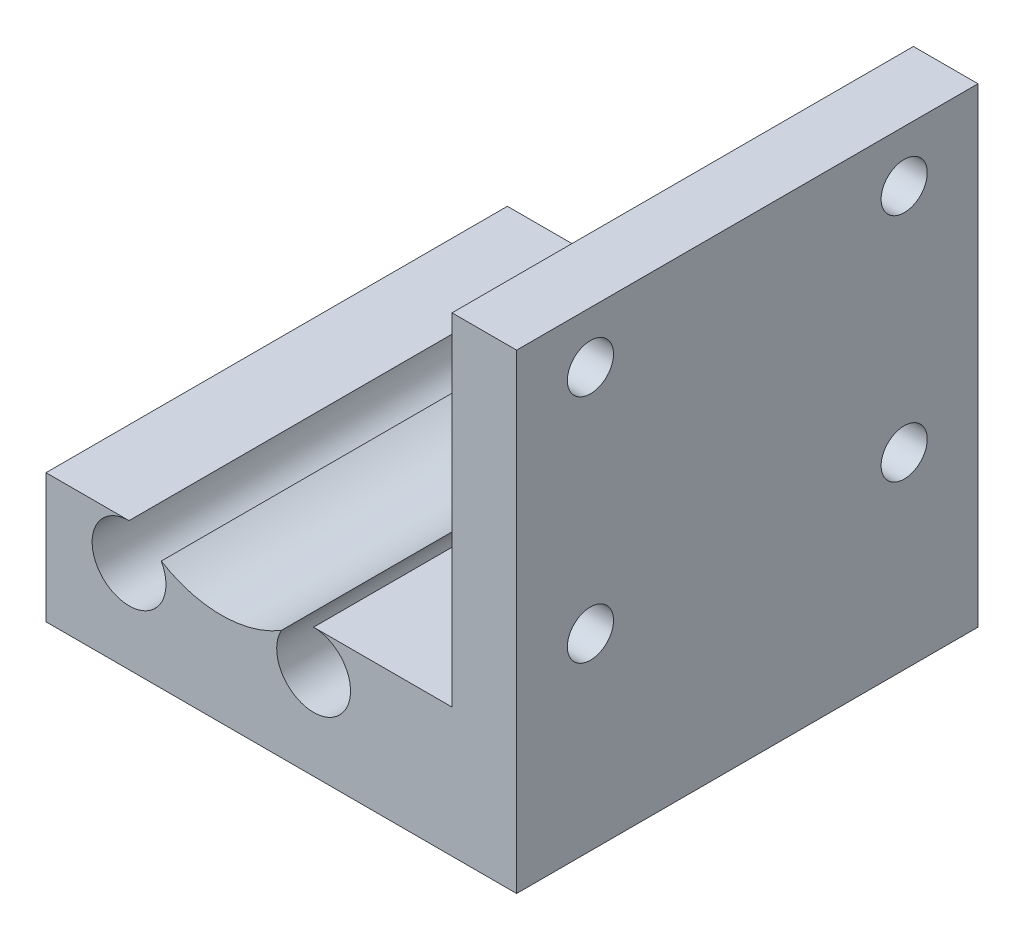
SolidWorks part; units mm, degrees
material "3.0517 (EN-AW 3003)"
ref_plane "Front Plane" through (0, 0, 0) normal (0, 0, 1) x (1, 0, 0)
ref_plane "Top Plane" through (0, 0, 0) normal (0, 1, 0) x (1, 0, 0)
ref_plane "Right Plane" through (0, 0, 0) normal (1, 0, 0) x (0, 0, -1)
sketch "Sketch1" plane through (0, 0, 0) normal (0, 0, 1) x (1, 0, 0)
  line L0 (0, 18.7548) -> (0, -19.4032) construction
  line L1 (-10, -9.1244) -> (-19, -9.1244)
  line L2 (-19, -9.1244) -> (-19, -23.1244)
  line L3 (-19, -23.1244) -> (32, -23.1244)
  line L5 (32, 27.8756) -> (25, 27.8756)
  line L6 (25, 27.8756) -> (25, -9.1244)
  line L7 (25, -9.1244) -> (10, -9.1244)
  line L11 (-23.1238, -13.7244) -> (85.8792, -13.7244) construction
  line L15 (32, 27.8756) -> (32, -23.1244)
  circle A1 centre (0, 0) radius 12.5 construction
  arc A2 (6.5091, -11.1715) -> (10, -9.1244) centre (10, -13.1244) ccw
  arc A4 (-6.5091, -11.1715) -> (-10, -9.1244) centre (-10, -13.1244) cw
  circle A5 centre (0, 11.4164) radius 22.5 construction
  arc A6 (-6.5091, -11.1715) -> (6.5091, -11.1715) centre (0, -0.5) ccw
  circle A8 centre (-10, -13.1244) radius 4 construction
  circle A9 centre (10, -13.1244) radius 4 construction
  dimension "D1" = 25
  dimension "D2" = 8
  dimension "D3" = 10
  dimension "D4" = 45
  dimension "D5" = 12.5
  dimension "D6" = 0.5
  dimension "D7" = 9
  dimension "D8" = 14
  dimension "D9" = 51
  dimension "D10" = 15
  dimension "D12" = 7
  dimension "D14" = 9.4
extrude "Boss-Extrude1" add sketch "Sketch1" along normal mid plane 50
sketch "Sketch5" plane through (32, 0, 0) normal (1, 0, 0) x (0, 0, -1)
  line L0 (0, 45.8756) -> (0, -19.1244) construction
  line L1 (0, 27.8756) -> (0, -23.1244) construction
  line L2 (-25, 2.3756) -> (25, 2.3756) construction
  line L3 (-25, -23.1244) -> (-25, 27.8756) construction
  line L4 (25, -23.1244) -> (25, 27.8756) construction
  line L5 (17, 2.3756) -> (17, -23.1244) construction
  line L6 (-25, -23.1244) -> (25, -23.1244) construction
  line L7 (0, -2.7244) -> (25, -2.7244) construction
  line L8 (0, 22.2756) -> (25, 22.2756) construction
  line L9 (17, 2.3756) -> (17, 27.8756) construction
  line L10 (-25, 27.8756) -> (25, 27.8756) construction
  circle A0 centre (17, -2.7244) radius 2.5
  circle A4 centre (17, 22.2756) radius 2.5
  circle A5 centre (-17, -2.7244) radius 2.5
  circle A6 centre (-17, 22.2756) radius 2.5
  dimension "D3" = 5
  dimension "D5" = 5
  dimension "D1" = 17
  dimension "D2" = 25
  dimension "D4" = 5.6
extrude "Cut-Extrude4" cut sketch "Sketch5" against normal blind 90
chamfer "Chamfer1" distance 2.7 angle 45 4 edges at (25, -0.2244, -17) (25, -0.2244, 17) (25, 24.7756, 17) (25, 24.7756, -17)
